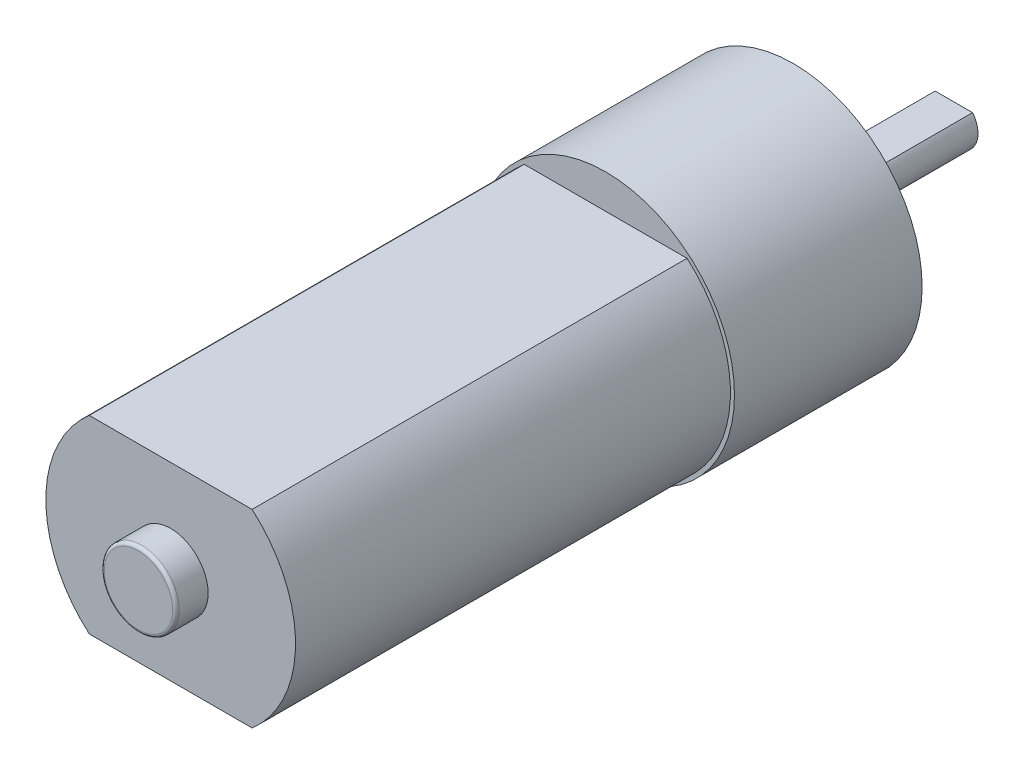
SolidWorks part; units mm, degrees
ref_plane "Front Plane" through (0, 0, 0) normal (0, 0, 1) x (1, 0, 0)
ref_plane "Top Plane" through (0, 0, 0) normal (0, 1, 0) x (1, 0, 0)
ref_plane "Right Plane" through (0, 0, 0) normal (1, 0, 0) x (0, 0, -1)
sketch "Sketch1" plane through (0, 0, 0) normal (0, 0, 1) x (1, 0, 0)
  circle A0 centre (0, 0) radius 8
  dimension "D1" = 16
extrude "Boss-Extrude1" add sketch "Sketch1" along normal blind 11.65
sketch "Sketch2" plane through (0, 0, 0) normal (0, 0, -1) x (-1, 0, 0)
  circle A0 centre (0, 0) radius 2.975
  dimension "D1" = 5.95
extrude "Boss-Extrude2" add sketch "Sketch2" along normal blind 1.82
sketch "Sketch3" plane through (0, 0, -1.82) normal (0, 0, -1) x (-1, 0, 0)
  circle A0 centre (0, 0) radius 1.5
  dimension "D1" = 3
extrude "Boss-Extrude3" add sketch "Sketch3" along normal blind 8.15
sketch "Sketch4" plane through (0, 0, -9.97) normal (0, 0, -1) x (-1, 0, 0)
  line L1 (-1.1608, 0.95) -> (1.1608, 0.95)
  line L2 (-1.1608, 0.95) -> (-1.1608, 2.1994)
  line L3 (-1.1608, 2.1994) -> (1.1608, 2.1994)
  line L4 (1.1608, 0.95) -> (1.1608, 2.1994)
  circle A0 centre (0, 0) radius 1.5 construction
  circle A1 centre (0, 0) radius 1.5 construction
  dimension "D1" = 0.95
extrude "Cut-Extrude1" cut sketch "Sketch4" against normal blind 7
sketch "Sketch5" plane through (0, 0, 11.65) normal (0, 0, 1) x (1, 0, 0)
  circle A0 centre (0, 0) radius 7.75
  dimension "D1" = 15.5
extrude "Boss-Extrude4" add sketch "Sketch5" along normal blind 27
sketch "Sketch6" plane through (0, 0, 38.65) normal (0, 0, 1) x (1, 0, 0)
  line L1 (-5.0544, -5.875) -> (5.0544, -5.875)
  line L2 (-5.0544, -5.875) -> (-5.0544, -8.4509)
  line L3 (-5.0544, -8.4509) -> (5.0544, -8.4509)
  line L4 (5.0544, -5.875) -> (5.0544, -8.4509)
  circle A0 centre (0, 0) radius 7.75 construction
  circle A1 centre (0, 0) radius 7.75 construction
  dimension "D1" = 5.875
extrude "Cut-Extrude2" cut sketch "Sketch6" against normal blind 27
mirror "Mirror1" about plane through (0, 0, 0) normal (0, 1, 0) of "Cut-Extrude2"
sketch "Sketch7" plane through (0, 0, 38.65) normal (0, 0, 1) x (1, 0, 0)
  circle A0 centre (0, 0) radius 2.325
  dimension "D1" = 4.65
extrude "Boss-Extrude6" add sketch "Sketch7" along normal blind 2
fillet "Fillet1" radius 0.2 1 edges at (2.325, 0, 40.65)
hole_wizard "Tap Drill for M2x0.4 Tap1" positions "Sketch10" profile "Sketch8" hole size "M2x0.4" standard "ANSI Metric"
sketch "Sketch10" plane through (0, 0, 0) normal (0, 0, -1) x (-1, 0, 0)
  circle A0 centre (0, 0) radius 5.5 construction
  point P0 (-5.5, 0)
  point P2 (5.5, 0)
  dimension "D1" = 11
sketch "Sketch8" plane through (5.5, 0, 0) normal (1, 0, 0) x (0, 1, 0)
  line L0 (0, 0) -> (0, 3.4807)
  line L1 (0, 3.4807) -> (0.8, 3)
  line L2 (0.8, 3) -> (0.8, 0)
  line L5 (0.8, 0) -> (0, 0)
  line L10 (0, 3.4807) -> (-0.8, 3) construction
  line L11 (0, -6.35) -> (0, 107.95) construction
  dimension "Hole Dia." = 1.6
  dimension "Hole Depth" = 3
  dimension "Drill Angle" = 118
